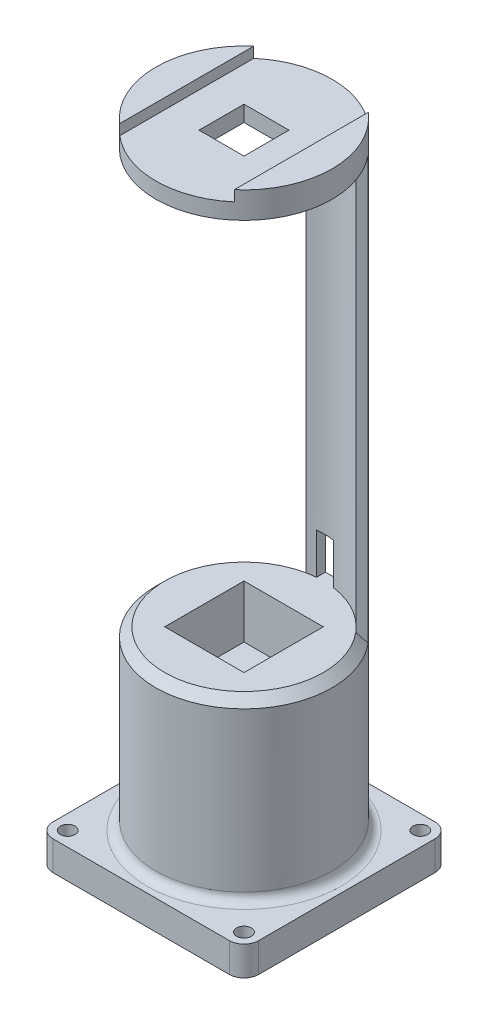
SolidWorks part; units mm, degrees
ref_plane "Front Plane" through (0, 0, 0) normal (0, 0, 1) x (1, 0, 0)
ref_plane "Top Plane" through (0, 0, 0) normal (0, 1, 0) x (1, 0, 0)
ref_plane "Right Plane" through (0, 0, 0) normal (1, 0, 0) x (0, 0, -1)
sketch "Sketch1" plane through (0, 0, 0) normal (0, 1, 0) x (1, 0, 0)
  line L1 (0, 0) -> (350, 0)
  line L2 (0, 0) -> (0, 350)
  line L3 (0, 350) -> (350, 350)
  line L4 (350, 0) -> (350, 350)
extrude "Boss-Extrude1" add sketch "Sketch1" against normal blind 50
fillet "Fillet1" radius 25 4 edges at (0, -25, -350) (350, -25, -350) (350, -25, 0) (0, -25, 0)
sketch "Sketch2" plane through (0, 0, 0) normal (0, 1, 0) x (1, 0, 0)
  circle A0 centre (25, 25) radius 12.5
  circle A1 centre (325, 25) radius 12.5
  circle A2 centre (325, 325) radius 12.5
  circle A3 centre (25, 325) radius 12.5
  dimension "D1" = 2
  dimension "D2" = 2
extrude "Cut-Extrude1" cut sketch "Sketch2" against normal blind 50
sketch "Sketch3" plane through (0, 0, 0) normal (0, 1, 0) x (1, 0, 0)
  circle A0 centre (175, 175) radius 150
extrude "Boss-Extrude2" add sketch "Sketch3" along normal blind 300
fillet "Fillet2" radius 15 1 edges at (175, 0, -325)
chamfer "Chamfer1" distance 15 angle 45 1 edges at (175, 300, -25)
sketch "Sketch5" plane through (0, 300, 0) normal (0, -1, 0) x (1, 0, 0)
  line L0 (107.5, -107.5) -> (242.5, -107.5)
  line L7 (107.5, -107.5) -> (107.5, -242.5)
  line L8 (242.5, -107.5) -> (242.5, -242.5)
  line L9 (107.5, -242.5) -> (242.5, -242.5)
  point P0 (175, -175)
  point P6 (175, -175)
extrude "Cut-Extrude3" cut sketch "Sketch5" along normal blind 90
scale "Scale1" scale about origin uniform scaling yes scale factor 0.333333
sketch "Sketch6" plane through (0, 100, 0) normal (0, 1, 0) x (1, 0, 0)
  arc A0 (48.3913, 107.3349) -> (96.6356, 90.4727) centre (58.3333, 58.3333) cw
  circle A1 centre (58.3333, 58.3333) radius 50 construction
  circle A2 centre (58.3333, 58.3333) radius 50 construction
extrude "Extrude-Thin1" add sketch "Sketch6" against normal blind 5 and the other way blind 250 thin
sketch "Sketch7" plane through (0, 350, 0) normal (0, 1, 0) x (1, 0, 0)
  circle A0 centre (58.3333, 58.3333) radius 50
extrude "Boss-Extrude3" add sketch "Sketch7" against normal blind 15 contours A0
sketch "Sketch8" plane through (0, 335, 0) normal (0, -1, 0) x (1, 0, 0)
  line L1 (45.5833, -71.0833) -> (71.0833, -71.0833)
  line L2 (45.5833, -71.0833) -> (45.5833, -45.5833)
  line L3 (45.5833, -45.5833) -> (71.0833, -45.5833)
  line L4 (71.0833, -71.0833) -> (71.0833, -45.5833)
  line L5 (45.5833, -71.0833) -> (71.0833, -45.5833) construction
  line L6 (45.5833, -45.5833) -> (71.0833, -71.0833) construction
  point P0 (58.3333, -58.3333)
extrude "Cut-Extrude4" cut sketch "Sketch8" against normal blind 9.5
sketch "Sketch9" plane through (0, 350, 0) normal (0, 1, 0) x (1, 0, 0)
  line L1 (90.8333, 108.3333) -> (25.8333, 108.3333)
  line L2 (90.8333, 108.3333) -> (90.8333, 8.3333)
  line L3 (90.8333, 8.3333) -> (25.8333, 8.3333)
  line L4 (25.8333, 108.3333) -> (25.8333, 8.3333)
  line L5 (90.8333, 108.3333) -> (25.8333, 8.3333) construction
  line L6 (90.8333, 8.3333) -> (25.8333, 108.3333) construction
  circle A0 centre (58.3333, 58.3333) radius 50 construction
  point P0 (58.3333, 58.3333)
extrude "Cut-Extrude5" cut sketch "Sketch9" against normal blind 6
sketch "Sketch10" plane through (0, 0, -80.8333) normal (0, 0, 1) x (1, 0, 0)
  line L0 (35.8333, 100) -> (80.8333, 100) construction
  line L1 (54.5756, 123.3333) -> (64.5756, 123.3333)
  line L2 (54.5756, 123.3333) -> (54.5756, 100)
  line L3 (54.5756, 100) -> (64.5756, 100)
  line L4 (64.5756, 123.3333) -> (64.5756, 100)
  line L5 (54.5756, 123.3333) -> (64.5756, 100) construction
  line L6 (54.5756, 100) -> (64.5756, 123.3333) construction
  point P0 (59.5756, 111.6667)
extrude "Cut-Extrude6" cut sketch "Sketch10" against normal through all
sketch "Sketch12" plane through (0, -16.6667, 0) normal (0, 1, 0) x (1, 0, 0)
  circle A0 centre (58.3333, 58.3333) radius 37.5
extrude "Cut-Extrude7" cut sketch "Sketch12" along normal blind 75
